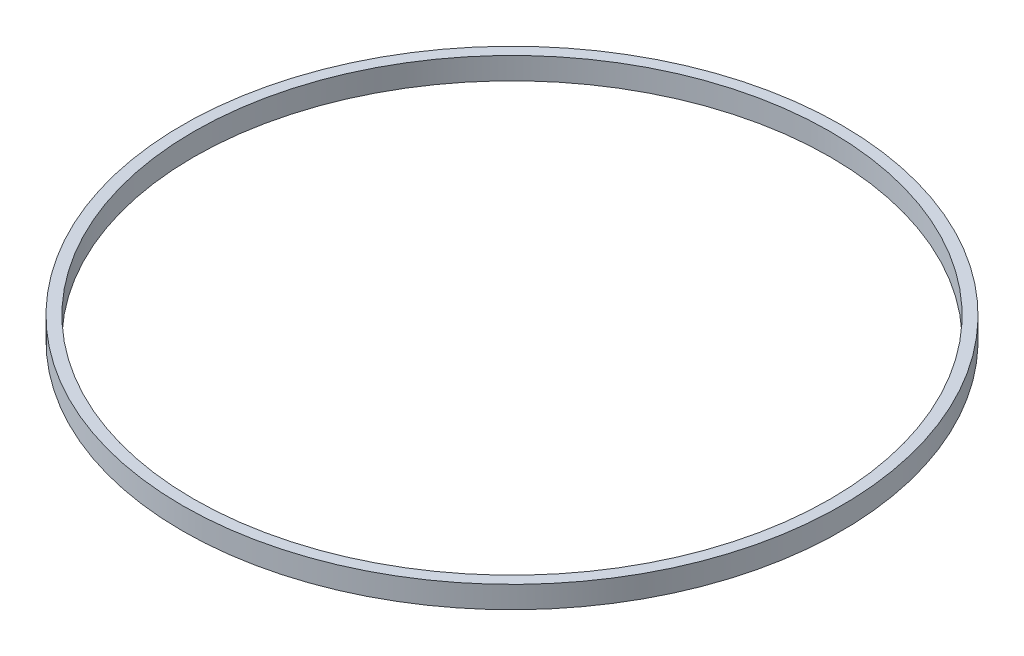
SolidWorks part; units mm, degrees
ref_plane "Front Plane" through (0, 0, 0) normal (0, 0, 1) x (1, 0, 0)
ref_plane "Top Plane" through (0, 0, 0) normal (0, 1, 0) x (1, 0, 0)
ref_plane "Right Plane" through (0, 0, 0) normal (1, 0, 0) x (0, 0, -1)
sketch "Sketch1" plane through (0, 0, 0) normal (0, 1, 0) x (1, 0, 0)
  circle A0 centre (0, 0) radius 1500
  circle A1 centre (0, 0) radius 1448.6474
  dimension "D1" = 3000
extrude "Boss-Extrude1" add sketch "Sketch1" along normal blind 100
